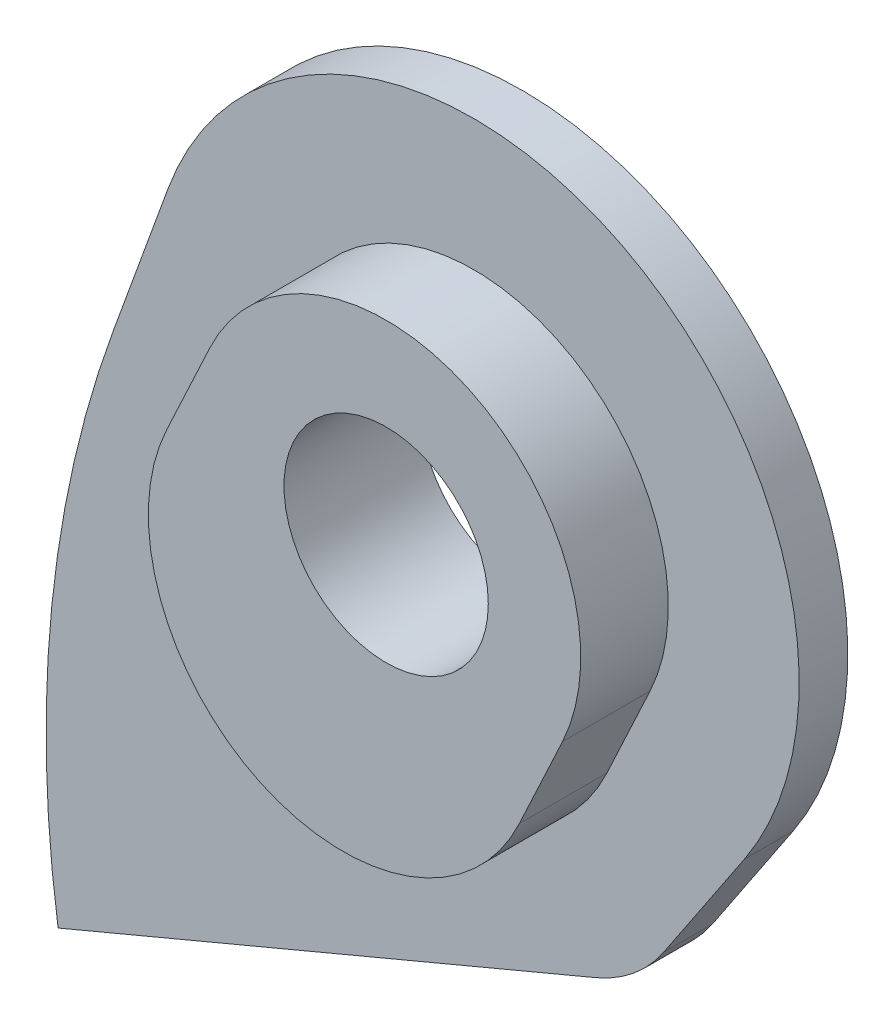
SolidWorks part; units mm, degrees
ref_plane "Front Plane" through (0, 0, 0) normal (0, 0, 1) x (1, 0, 0)
ref_plane "Top Plane" through (0, 0, 0) normal (0, 1, 0) x (1, 0, 0)
ref_plane "Right Plane" through (0, 0, 0) normal (1, 0, 0) x (0, 0, -1)
sketch "Sketch6" plane through (0, 0, 0) normal (0, 0, 1) x (1, 0, 0)
  line L0 (0, 0) -> (40.1809, 0) construction
  line L1 (0, 0) -> (35.507, 92.499) construction
  line L2 (19.3519, 50.4133) -> (0.4719, 63.0164) construction
  line L3 (19.3519, 50.4133) -> (-36.1025, 71.7003) construction
  dimension "D1" = 69
  dimension "D2" = 54
  dimension "D3" = 22.7
  dimension "D4" = 5
sketch "Sketch3" plane through (0, 0, 0) normal (0, 0, 1) x (1, 0, 0)
  line L0 (24.1743, 72.523) -> (120.8717, 72.523) construction
  line L6 (11.8164, 60.2529) -> (11.7284, 60.3116)
  line L7 (7.3748, 53.5992) -> (5.9136, 54.5745)
  line L8 (19.3519, 50.4133) -> (0.4719, 63.0164) construction
  line L9 (-6.1719, 82.4206) -> (-7.2903, 79.3479)
  line L10 (19.3519, 50.4133) -> (13.2479, 41.2693) construction
  line L11 (19.3519, 50.4133) -> (31.6629, 68.8558) construction
  line L12 (4.0204, 73.9337) -> (5.6789, 76.4182)
  line L14 (0.1147, 80.1325) -> (27.1455, 62.0885) construction
  line L15 (0.1147, 80.1325) -> (-7.2903, 79.3479) construction
  line L16 (0.1147, 80.1325) -> (0.1147, 91.1913) construction
  line L17 (0.1147, 80.1325) -> (-6.1719, 82.4206) construction
  arc A0 (13.4996, 47.0498) -> (20.2139, 57.1081) centre (19.3519, 50.4133) ccw
  arc A1 (20.2139, 57.1081) -> (11.8164, 60.2529) centre (22.7223, 76.5904) cw
  arc A2 (13.4996, 47.0498) -> (7.3748, 53.5992) centre (-3.5311, 37.2616) ccw
  arc A3 (11.7284, 60.3116) -> (6.8662, 65.9311) centre (19.4923, 71.9424) cw
  arc A4 (-6.1719, 82.4206) -> (5.6789, 76.4182) centre (0.1147, 80.1325) cw
  arc A5 (6.8662, 65.9311) -> (4.9012, 68.3908) centre (0.6246, 62.9595) ccw
  arc A6 (4.9012, 68.3908) -> (4.0204, 73.9337) centre (7.4585, 71.6386) cw
  arc A7 (5.9136, 54.5745) -> (0.4148, 56.2666) centre (0.3298, 46.2096) ccw
  arc A10 (0.4148, 56.2666) -> (-5.2798, 59.4837) centre (0.4719, 63.0164) cw
  circle A12 centre (19.3519, 50.4133) radius 2.75
  circle A13 centre (0.4719, 63.0164) radius 2.75
  circle A17 centre (0.1147, 80.1325) radius 2.1
  arc A18 (-7.2903, 79.3479) -> (-5.2798, 59.4837) centre (14.2795, 71.4971) ccw
  dimension "D1" = 5.5
  dimension "D2" = 5.5
  dimension "D3" = 4
  dimension "D5" = 4
  dimension "D6" = 4
  dimension "D4" = 4.2
  dimension "D17" = 70
  dimension "D18" = 3.27
  dimension "D14" = 6.69
  dimension "D7" = 3
  dimension "D8" = 4
  dimension "D9" = 3
  dimension "D10" = 4
  dimension "D11" = 19
  dimension "D12" = 19
  dimension "D13" = 22
  dimension "D15" = 32.5
  dimension "D16" = 14
extrude "Boss-Extrude2" add sketch "Sketch3" along normal blind 11
sketch "Sketch13" plane through (0, 0, 0) normal (0, 0, -1) x (-1, 0, 0)
  line L0 (-5.6789, 76.4182) -> (-4.0204, 73.9337)
  line L1 (-2.6258, 72.7829) -> (8.4277, 68.1397)
  line L2 (6.1719, 82.4206) -> (7.2903, 79.3479)
  arc A0 (-5.6789, 76.4182) -> (6.1719, 82.4206) centre (-0.1147, 80.1325) cw
  arc A1 (6.1719, 82.4206) -> (-5.6789, 76.4182) centre (-0.1147, 80.1325) ccw construction
  arc A2 (-4.0204, 73.9337) -> (-2.6258, 72.7829) centre (-1.4106, 75.6758) ccw
  arc A3 (5.2798, 59.4837) -> (7.2903, 79.3479) centre (-14.2795, 71.4971) ccw construction
  arc A4 (8.4277, 68.1397) -> (7.2903, 79.3479) centre (-14.2795, 71.4971) ccw
extrude "Boss-Extrude4" add sketch "Sketch13" along normal blind 1
sketch "Sketch12" plane through (0, 0, -1) normal (0, 0, -1) x (-1, 0, 0)
  line L0 (8.0136, 76.9658) -> (4.9242, 69.6114)
  line L4 (4.9242, 69.6114) -> (8.4277, 68.1397)
  line L5 (-2.6258, 72.7829) -> (8.4277, 68.1397) construction
  line L8 (-2.6258, 72.7829) -> (8.4277, 68.1397) construction
  arc A0 (8.0136, 76.9658) -> (8.4277, 68.1397) centre (-14.2795, 71.4971) cw
  arc A1 (5.2798, 59.4837) -> (8.4277, 68.1397) centre (-14.2795, 71.4971) ccw construction
  dimension "D1" = 3.8
  dimension "D2" = 90
extrude "Boss-Extrude3" add sketch "Sketch12" along normal blind 3
sketch "Sketch14" plane through (0, 0, 0) normal (0, 1, 0) x (1, 0, 0)
  line L0 (19.3519, 0) -> (-36.1025, 0) construction
  line L1 (-15.2308, 0) -> (32.0549, 0)
  line L2 (-15.2308, 0) -> (-15.2308, -12.5955)
  line L3 (-15.2308, -12.5955) -> (32.0549, -12.5955)
  line L4 (32.0549, 0) -> (32.0549, -12.5955)
extrude "Cut-Extrude1" cut sketch "Sketch14" along normal through all
sketch "Sketch16" plane through (0, 0, 0) normal (0, 0, 1) x (1, 0, 0)
  line L0 (0.1147, 80.1325) -> (-0.7728, 78.2293) construction
  line L1 (3.7399, 78.4421) -> (2.8524, 76.5388)
  line L2 (-3.5105, 81.823) -> (-4.398, 79.9198)
  line L3 (0.1147, 80.1325) -> (0.1147, 75.6752) construction
  arc A0 (3.7399, 78.4421) -> (-3.5105, 81.823) centre (0.1147, 80.1325) ccw
  arc A1 (-4.398, 79.9198) -> (2.8524, 76.5388) centre (-0.7728, 78.2293) ccw
  point P3 (-0.3291, 79.1809)
  dimension "D1" = 4
  dimension "D2" = 25
  dimension "D3" = 2.1
extrude "Boss-Extrude5" add sketch "Sketch16" along normal blind 1.8
sketch "Sketch15" plane through (0, 0, 1.8) normal (0, 0, 1) x (1, 0, 0)
  circle A0 centre (0.1147, 80.1325) radius 2.1
  dimension "D1" = 4.2
extrude "Cut-Extrude2" cut sketch "Sketch15" against normal through all
